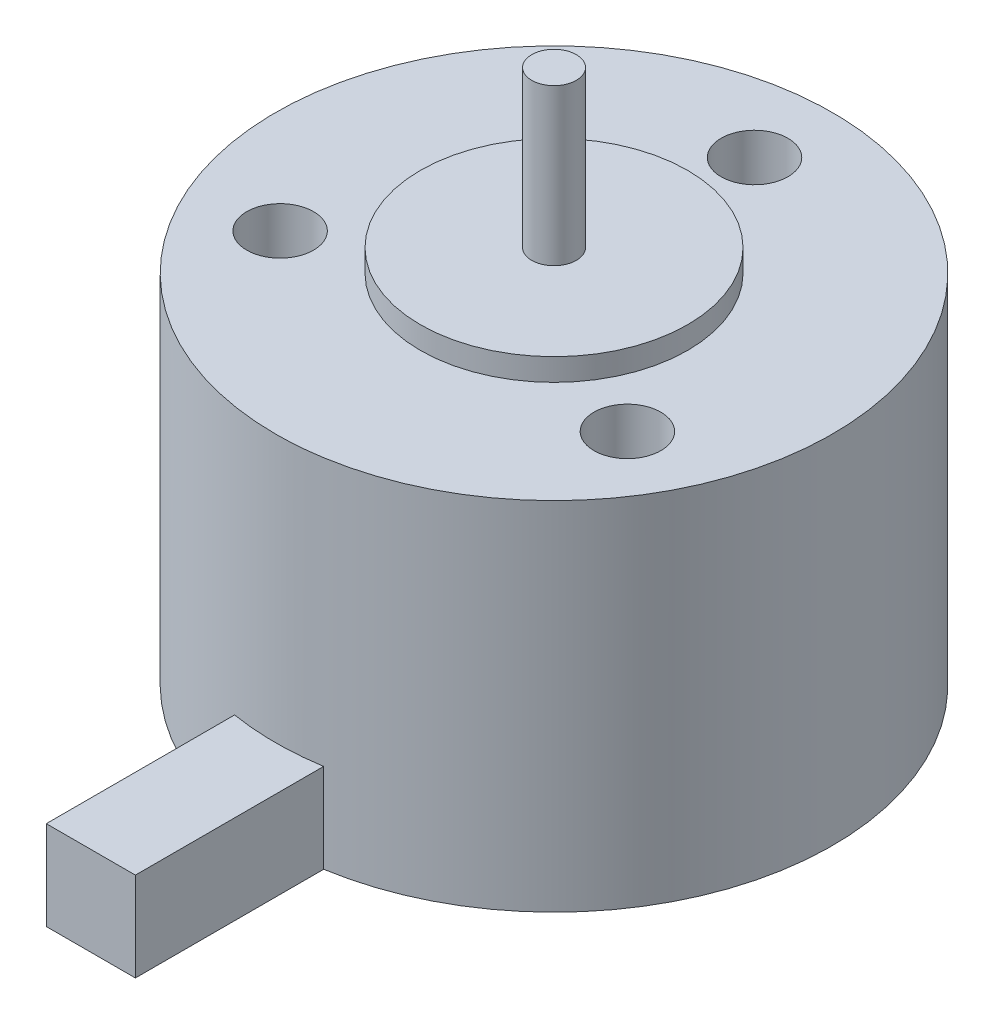
SolidWorks part; units mm, degrees
ref_plane "Plan de face" through (0, 0, 0) normal (0, 0, 1) x (1, 0, 0)
ref_plane "Plan de dessus" through (0, 0, 0) normal (0, 1, 0) x (1, 0, 0)
ref_plane "Plan de droite" through (0, 0, 0) normal (1, 0, 0) x (0, 0, -1)
sketch "Esquisse1" plane through (0, 0, 0) normal (0, 1, 0) x (1, 0, 0)
  circle A0 centre (0, 0) radius 12.5
  dimension "D1" = 25
extrude "Boss.-Extru.1" add sketch "Esquisse1" along normal blind 16
sketch "Esquisse2" plane through (0, 16, 0) normal (0, 1, 0) x (1, 0, 0)
  circle A0 centre (0, 0) radius 1
extrude "Boss.-Extru.2" add sketch "Esquisse2" along normal blind 8
sketch "Esquisse4" plane through (0, 0, 0) normal (0, -1, 0) x (1, 0, 0)
  line L0 (0, 0) -> (0, 25.4295) construction
  line L2 (0, 20.7906) -> (2, 20.7906)
  line L4 (0, 9.4927) -> (2, 9.4927)
  line L5 (2, 20.7906) -> (2, 9.4927)
  line L6 (0, 20.7906) -> (-2, 20.7906)
  line L8 (0, 9.4927) -> (-2, 9.4927)
  line L9 (-2, 20.7906) -> (-2, 9.4927)
  dimension "D1" = 2
  dimension "D2" = 2
extrude "Boss.-Extru.3" add sketch "Esquisse4" against normal blind 4
sketch "Esquisse5" plane through (0, 16, 0) normal (0, 1, 0) x (1, 0, 0)
  line L0 (0, -12.5) -> (0, 12.5) construction
  circle A0 centre (0, 0) radius 12.5 construction
  circle A1 centre (0, 9) radius 1.5
  circle A2 centre (0, 0) radius 1 construction
  dimension "D1" = 3
  dimension "D2" = 9
extrude "Enlèv. mat.-Extru.1" cut sketch "Esquisse5" against normal blind 5
pattern_circular "Répétition circulaire1" count 3 every 120 about axis through (0, 0, 0) along (0, 1, 0) of "Enlèv. mat.-Extru.1"
sketch "Esquisse6" plane through (0, 16, 0) normal (0, 1, 0) x (1, 0, 0)
  circle A0 centre (0, 0) radius 6
  dimension "D1" = 12
extrude "Boss.-Extru.4" add sketch "Esquisse6" along normal blind 1
